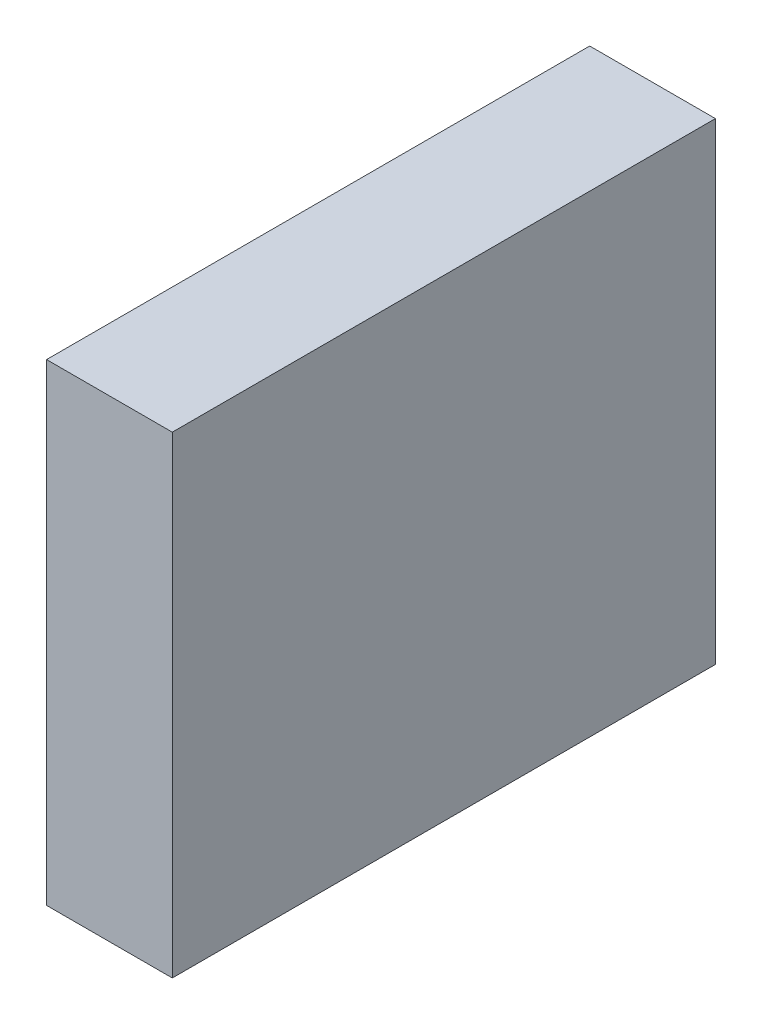
SolidWorks part; units mm, degrees
material "3d打印 35%"
ref_plane "前视基准面" through (0, 0, 0) normal (0, 0, 1) x (1, 0, 0)
ref_plane "上视基准面" through (0, 0, 0) normal (0, 1, 0) x (1, 0, 0)
ref_plane "右视基准面" through (0, 0, 0) normal (1, 0, 0) x (0, 0, -1)
other "Configuration Table"
sketch "草图1" plane through (0, 0, 0) normal (0, 0, 1) x (1, 0, 0)
  line L0 (0, 0) -> (25, 0)
  line L1 (25, 0) -> (25, 94)
  line L2 (25, 94) -> (0, 94)
  line L3 (0, 94) -> (0, 0)
  dimension "D1" = 25
  dimension "D2" = 94
extrude "凸台-拉伸1" add sketch "草图1" along normal blind 108
shell "抽壳2" thickness 4
